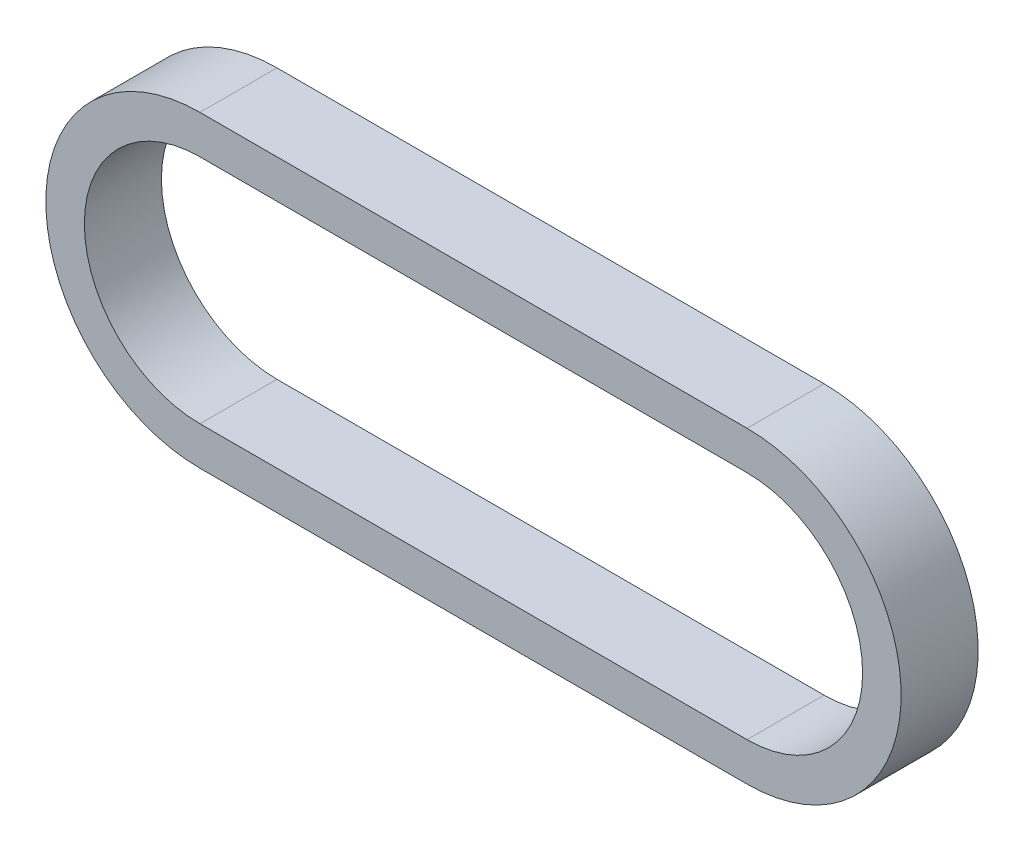
SolidWorks part; units mm, degrees
material "ﾌﾞﾁﾙ(BUTYL)"
ref_plane "正面" through (0, 0, 0) normal (0, 0, 1) x (1, 0, 0)
ref_plane "平面" through (0, 0, 0) normal (0, 1, 0) x (1, 0, 0)
ref_plane "右側面" through (0, 0, 0) normal (1, 0, 0) x (0, 0, -1)
sketch "ｽｹｯﾁ1" plane through (0, 0, 0) normal (0, 0, 1) x (1, 0, 0)
  line L0 (0, 0) -> (71, 0) construction
  line L1 (0, 15) -> (71, 15)
  line L2 (0, -15) -> (71, -15)
  line L3 (0, 20) -> (71, 20)
  line L4 (0, -20) -> (71, -20)
  arc A0 (0, 15) -> (0, -15) centre (0, 0) ccw
  arc A1 (71, -15) -> (71, 15) centre (71, 0) ccw
  arc A2 (71, -20) -> (71, 20) centre (71, 0) ccw
  arc A3 (0, 20) -> (0, -20) centre (0, 0) ccw
  point P3 (35.5, 0)
  dimension "D1" = 15
  dimension "D2" = 71
  dimension "D3" = 5
extrude "ﾎﾞｽ - 押し出し1" add sketch "ｽｹｯﾁ1" along normal blind 10
